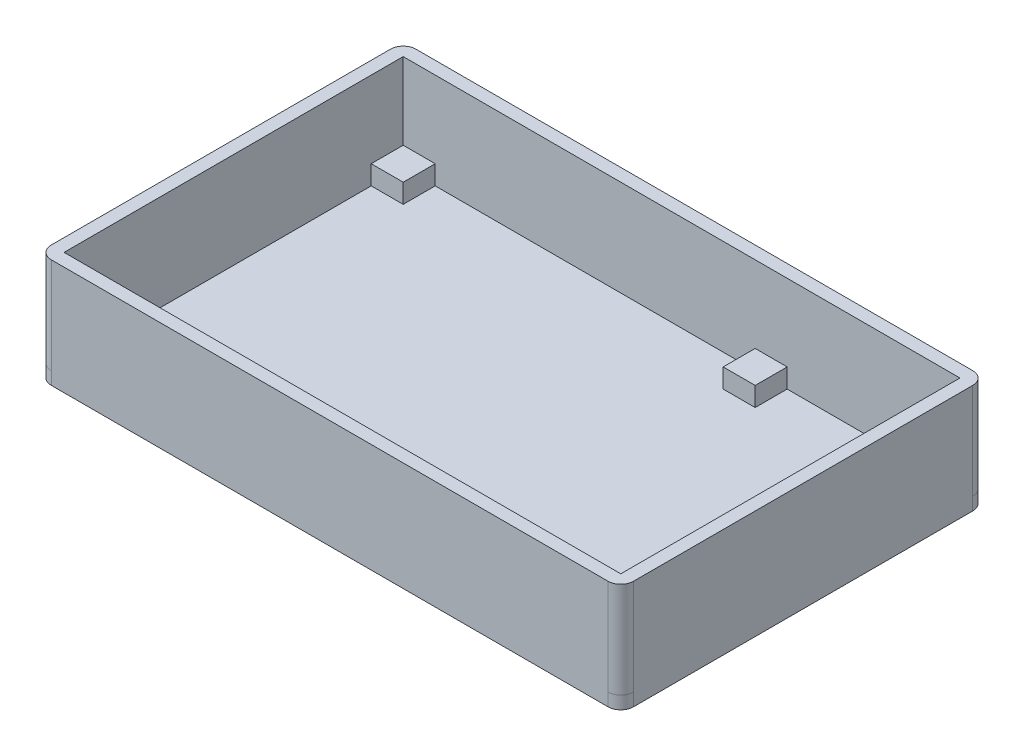
SolidWorks part; units mm, degrees
ref_plane "Front Plane" through (0, 0, 0) normal (0, 0, 1) x (1, 0, 0)
ref_plane "Top Plane" through (0, 0, 0) normal (0, 1, 0) x (1, 0, 0)
ref_plane "Right Plane" through (0, 0, 0) normal (1, 0, 0) x (0, 0, -1)
sketch "Sketch1" plane through (0, 0, 0) normal (0, 1, 0) x (1, 0, 0)
  line L1 (0, 0) -> (91, 0)
  line L2 (0, 0) -> (0, 57)
  line L3 (0, 57) -> (91, 57)
  line L4 (91, 0) -> (91, 57)
  dimension "D1" = 57
  dimension "D2" = 91
extrude "Boss-Extrude1" add sketch "Sketch1" along normal blind 2
sketch "Sketch2" plane through (0, 2, 0) normal (0, 1, 0) x (1, 0, 0)
  line L0 (0, 57) -> (0, 0) construction
  line L1 (2, 55) -> (89, 55)
  line L2 (2, 55) -> (2, 2)
  line L3 (2, 2) -> (89, 2)
  line L4 (89, 55) -> (89, 2)
  line L5 (91, 57) -> (0, 57) construction
  line L6 (91, 0) -> (91, 57) construction
  line L7 (0, 0) -> (91, 0) construction
  line L8 (2, 51.5) -> (5.5, 51.5)
  line L9 (0, 57) -> (91, 57)
  line L10 (0, 57) -> (0, 0)
  line L11 (0, 0) -> (91, 0)
  line L12 (91, 57) -> (91, 0)
  line L13 (5.5, 51.5) -> (5.5, 55)
  line L14 (85.5, 55) -> (85.5, 51.5)
  line L15 (85.5, 51.5) -> (89, 51.5)
  line L16 (89, 5.5) -> (85.5, 5.5)
  line L17 (85.5, 5.5) -> (85.5, 2)
  line L18 (5.5, 2) -> (5.5, 5.5)
  line L19 (5.5, 5.5) -> (2, 5.5)
  line M5 (0, 57) -> (0, 0)
  line M6 (0, 0) -> (91, 0)
  line M7 (91, 0) -> (91, 57)
  line M8 (91, 57) -> (0, 57)
  dimension "D1" = 2
  dimension "D2" = 2
  dimension "D3" = 2
  dimension "D4" = 2
  dimension "D5" = 3.5
  dimension "D6" = 3.5
  dimension "D7" = 3.5
  dimension "D8" = 3.5
  dimension "D9" = 3.5
  dimension "D10" = 3.5
  dimension "D11" = 3.5
  dimension "D12" = 3.5
fillet "Fillet1" radius 2 4 edges at (0, 1, -57) (91, 1, -57) (91, 1, 0) (0, 1, 0)
extrude "Boss-Extrude6" add sketch "Sketch2" along normal blind 15 contours L1 L4 L3 L2 M8 M5 M6 M7
fillet "Fillet2" radius 2 4 edges at (0, 9.5, -57) (91, 9.5, -57) (91, 9.5, 0) (0, 9.5, 0)
sketch "Sketch13" plane through (0, 2, 0) normal (0, 1, 0) x (1, 0, 0)
  line L0 (2, 55) -> (89, 55) construction
  line L1 (2, 55) -> (7, 55)
  line L2 (2, 55) -> (2, 50)
  line L3 (2, 50) -> (7, 50)
  line L4 (7, 55) -> (7, 50)
  line L5 (2, 2) -> (7, 2)
  line L6 (2, 2) -> (2, 7)
  line L7 (2, 7) -> (7, 7)
  line L8 (7, 2) -> (7, 7)
  line L9 (57, 55) -> (62, 55)
  line L10 (57, 55) -> (57, 50)
  line L11 (57, 50) -> (62, 50)
  line L12 (62, 55) -> (62, 50)
  line L13 (2, 2) -> (89, 2) construction
  line L14 (57, 2) -> (62, 2)
  line L15 (57, 2) -> (57, 7)
  line L16 (57, 7) -> (62, 7)
  line L17 (62, 2) -> (62, 7)
  point P22 (0, 0)
  point P23 (0, 0)
  dimension "D1" = 5
  dimension "D2" = 5
  dimension "D3" = 5
  dimension "D4" = 5
  dimension "D5" = 5
  dimension "D6" = 5
  dimension "D7" = 5
  dimension "D8" = 5
  dimension "D9" = 60
  dimension "D10" = 60
extrude "Boss-Extrude7" add sketch "Sketch13" along normal blind 3
